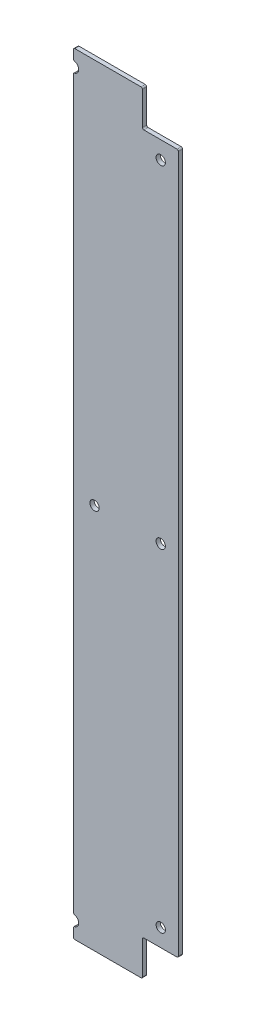
SolidWorks part; units mm, degrees
material "Acrylic (Medium-high impact)"
ref_plane "Front Plane" through (0, 0, 0) normal (0, 0, 1) x (1, 0, 0)
ref_plane "Top Plane" through (0, 0, 0) normal (0, 1, 0) x (1, 0, 0)
ref_plane "Right Plane" through (0, 0, 0) normal (1, 0, 0) x (0, 0, -1)
sketch "Sketch1" plane through (0, 0, 0) normal (0, 0, 1) x (1, 0, 0)
  line L0 (25.5, 522.5) -> (25.5, -25.5)
  line L1 (25.5, -25.5) -> (74.5, -25.5)
  line L3 (25.5, 522.5) -> (74.5, 522.5)
  line L4 (100, 0) -> (100, 497)
  line L7 (100, 0) -> (74.5, 0)
  line L8 (74.5, -25.5) -> (74.5, 0)
  line L19 (100, 497) -> (74.5, 497)
  line L20 (74.5, 522.5) -> (74.5, 497)
  dimension "D1" = 74.5
  dimension "D2" = 548
  dimension "D3" = 25.5
extrude "Boss-Extrude1" add sketch "Sketch1" along normal blind 3
hole_wizard "M6 Clearance Hole1" positions "Sketch2" profile "Sketch3" hole size "M6" standard "ANSI Metric" end condition up to next
sketch "Sketch2" plane through (0, 0, 0) normal (0, 0, -1) x (-1, 0, 0)
  line L1 (-100, 0) -> (-100, 497) construction
  line L2 (-74.5, 0) -> (-100, 0) construction
  line L3 (-100, 497) -> (-74.5, 497) construction
  point P0 (-87.5, 12.5)
  point P4 (-87.5, 484.5)
  point P34 (-87.5, 248.5)
  point P37 (0, 0)
  point P38 (-100, 248.5)
  point P39 (0, 0)
  dimension "D2" = 12.5
  dimension "D3" = 12.5
  dimension "D4" = 12.5
sketch "Sketch3" plane through (87.5, 12.5, 0) normal (1, 0, 0) x (0, 1, 0)
  line L0 (0, 0) -> (0, 3)
  line L1 (0, 3) -> (3.3, 3)
  line L2 (3.3, 3) -> (3.3, 0)
  line L5 (3.3, 0) -> (0, 0)
  line L11 (0, -6.35) -> (0, 107.95) construction
  dimension "Thru Hole Dia." = 6.6
  dimension "Thru Hole Depth" = 3
hole_wizard "M6 Clearance Hole2" positions "Sketch4" profile "Sketch5" hole size "M6" standard "ANSI Metric" end condition up to next
sketch "Sketch4" plane through (0, 0, 0) normal (0, 0, -1) x (-1, 0, 0)
  point P0 (-40.5, 248.5)
  point P7 (0, 0)
sketch "Sketch5" plane through (40.5, 248.5, 0) normal (1, 0, 0) x (0, 1, 0)
  line L0 (0, 0) -> (0, 3)
  line L1 (0, 3) -> (3.3, 3)
  line L2 (3.3, 3) -> (3.3, 0)
  line L5 (3.3, 0) -> (0, 0)
  line L11 (0, -6.35) -> (0, 107.95) construction
  dimension "Thru Hole Dia." = 6.6
  dimension "Thru Hole Depth" = 3
sketch "Sketch6" plane through (0, 0, 0) normal (0, 0, -1) x (-1, 0, 0)
  line L0 (-25.5, 522.5) -> (-25.5, -25.5) construction
  line L1 (-25.5, -25.5) -> (-74.5, -25.5) construction
  line L2 (-74.5, 522.5) -> (-25.5, 522.5) construction
  circle A0 centre (-25.5, -14) radius 3.75
  circle A1 centre (-25.5, 511) radius 3.75
  point P6 (0, 0)
  dimension "D2" = 7.5
  dimension "D1" = 11.5
  dimension "D3" = 11.5
extrude "Cut-Extrude1" cut sketch "Sketch6" against normal through all
fillet "Fillet1" radius 1 12 edges at (100, 497, 1.5) (74.5, 497, 1.5) (74.5, 522.5, 1.5) (25.5, 522.5, 1.5) (25.5, 514.75, 1.5) (25.5, 507.25, 1.5) (25.5, -10.25, 1.5) (25.5, -17.75, 1.5) (25.5, -25.5, 1.5) (74.5, -25.5, 1.5) (74.5, 0, 1.5) (100, 0, 1.5)
